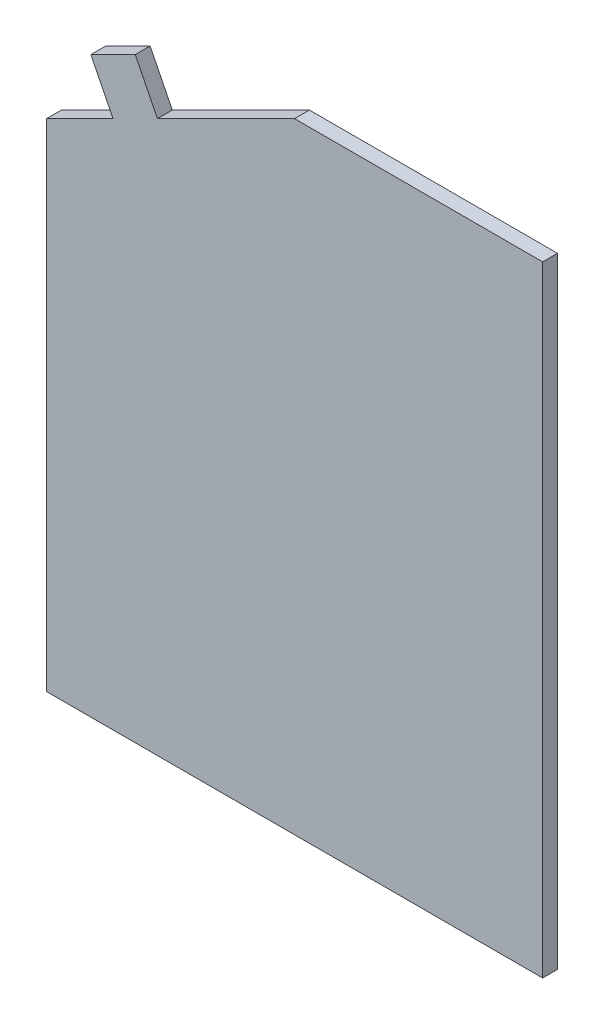
SolidWorks part; units mm, degrees
ref_plane "Plan de face" through (0, 0, 0) normal (0, 0, 1) x (1, 0, 0)
ref_plane "Plan de dessus" through (0, 0, 0) normal (0, 1, 0) x (1, 0, 0)
ref_plane "Plan de droite" through (0, 0, 0) normal (1, 0, 0) x (0, 0, -1)
sketch "Esquisse1" plane through (0, 0, 0) normal (0, 0, 1) x (1, 0, 0)
  line L0 (0, 0) -> (100, 0)
  line L1 (0, 0) -> (0, 100)
  line L2 (0, 100) -> (100, 150) construction
  line L4 (100, 150) -> (100, 0) construction
  line L5 (22.3607, 111.1803) -> (13.4164, 106.7082) construction
  line L6 (22.3607, 111.1803) -> (17.8885, 120.1246)
  line L7 (13.4164, 106.7082) -> (8.9443, 115.6525)
  line L8 (17.8885, 120.1246) -> (8.9443, 115.6525)
  line L9 (0, 100) -> (13.4164, 106.7082)
  line L10 (22.3607, 111.1803) -> (100, 150) construction
  line L11 (50, 125) -> (100, 125)
  line L12 (22.3607, 111.1803) -> (50, 125)
  line L13 (100, 125) -> (100, 0)
  dimension "D1" = 100
  dimension "D2" = 150
  dimension "D3" = 100
  dimension "D4" = 10
  dimension "D5" = 10
  dimension "D6" = 15
  dimension "D7" = 25
extrude "Boss.-Extru.1" add sketch "Esquisse1" along normal blind 3
